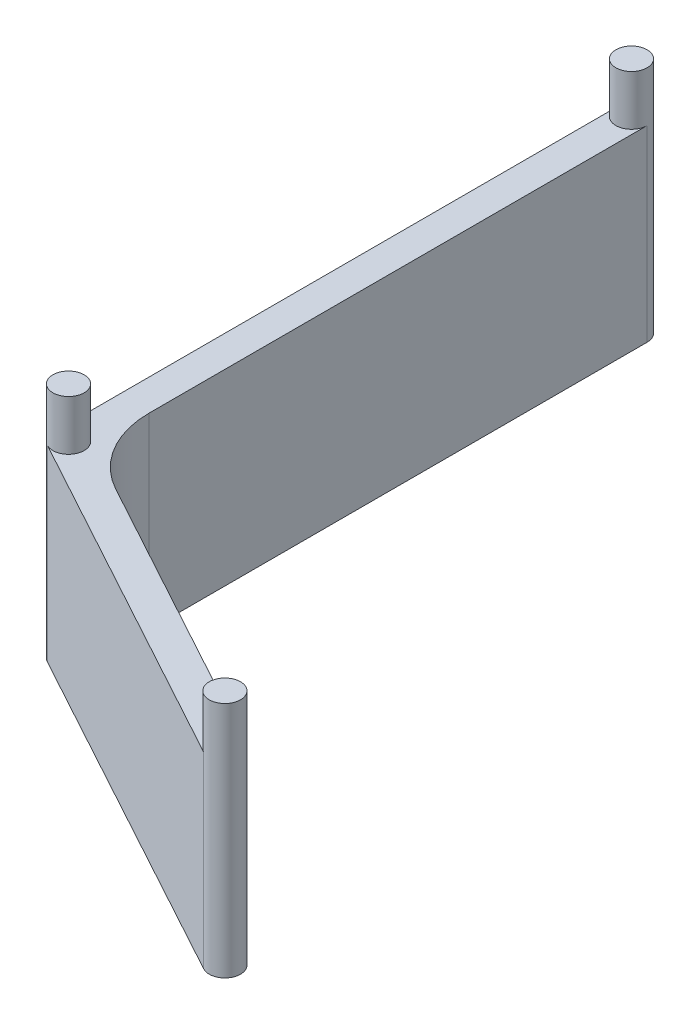
SolidWorks part; units mm, degrees
material "ABS"
ref_plane "Front Plane" through (0, 0, 0) normal (0, 0, 1) x (1, 0, 0)
ref_plane "Top Plane" through (0, 0, 0) normal (0, 1, 0) x (1, 0, 0)
ref_plane "Right Plane" through (0, 0, 0) normal (1, 0, 0) x (0, 0, -1)
sketch "Sketch1" plane through (0, 0, 0) normal (0, 1, 0) x (1, 0, 0)
  line L0 (0, 0) -> (0, 114.3) construction
  line L1 (-3.175, 0) -> (-3.175, 114.3)
  line L2 (3.175, 1.8848) -> (3.175, 114.3)
  line L3 (0, 0) -> (69.85, -38.1) construction
  line L4 (3.175, 1.8848) -> (71.3704, -35.3127)
  line L5 (-1.5204, -2.7873) -> (68.3296, -40.8873)
  arc A0 (-3.175, 0) -> (-1.5204, -2.7873) centre (0, 0) ccw
  arc A1 (3.175, 114.3) -> (-3.175, 114.3) centre (0, 114.3) ccw
  arc A3 (68.3296, -40.8873) -> (71.3704, -35.3127) centre (69.85, -38.1) ccw
  point P3 (0, 57.15)
  point P8 (34.925, -19.05)
  dimension "D1" = 6.35
  dimension "D2" = 6.35
  dimension "D3" = 152.4
  dimension "D4" = 114.3
  dimension "D5" = 69.85
extrude "Boss-Extrude1" add sketch "Sketch1" along normal blind 38.1
sketch "Sketch2" plane through (0, 0, 0) normal (0, -1, 0) x (-1, 0, 0)
  circle A0 centre (0, 114.3) radius 3.175
  circle A1 centre (0, 0) radius 3.175
  circle A2 centre (-69.85, -38.1) radius 3.175
extrude "Boss-Extrude2" add sketch "Sketch2" against normal blind 48.26
fillet "Fillet1" radius 19.05 1 edges at (3.175, 19.05, -1.8848)
